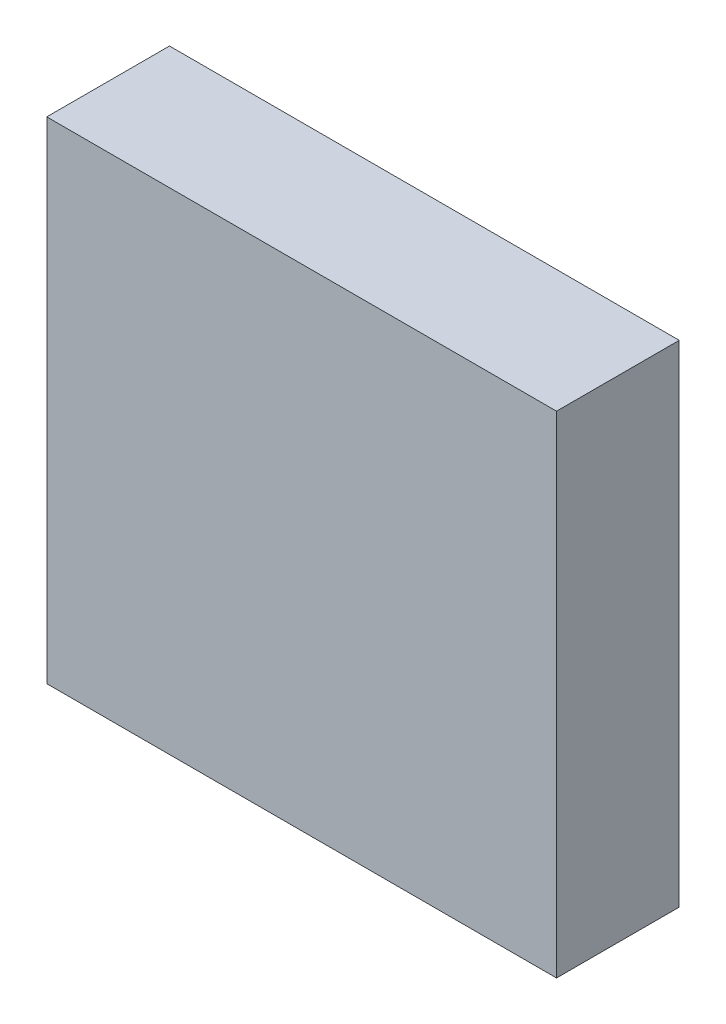
SolidWorks part; units mm, degrees
ref_plane "Front Plane" through (0, 0, 0) normal (0, 0, 1) x (1, 0, 0)
ref_plane "Top Plane" through (0, 0, 0) normal (0, 1, 0) x (1, 0, 0)
ref_plane "Right Plane" through (0, 0, 0) normal (1, 0, 0) x (0, 0, -1)
sketch "Sketch1" plane through (0, 0, 0) normal (0, 0, 1) x (1, 0, 0)
  line L1 (-13.5, 13) -> (13.5, 13)
  line L2 (-13.5, 13) -> (-13.5, -13)
  line L3 (-13.5, -13) -> (13.5, -13)
  line L4 (13.5, 13) -> (13.5, -13)
  line L5 (-13.5, 13) -> (13.5, -13) construction
  line L6 (-13.5, -13) -> (13.5, 13) construction
  point P0 (0, 0)
  dimension "D1" = 27
  dimension "D2" = 26
extrude "Boss-Extrude1" add sketch "Sketch1" along normal mid plane 6.5
